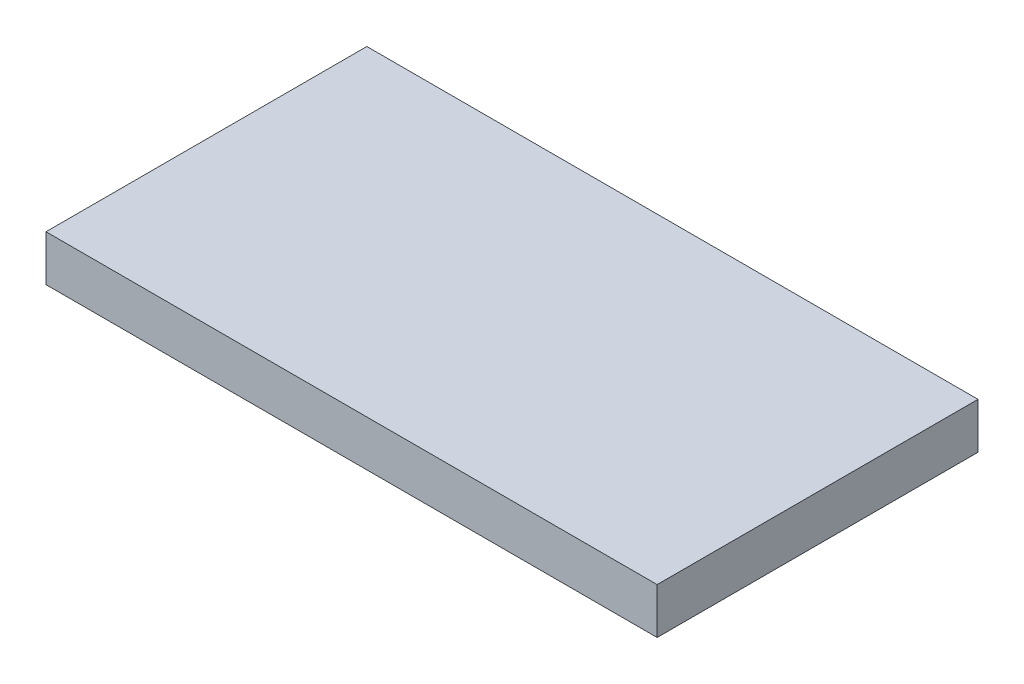
SolidWorks part; units mm, degrees
ref_plane "Front Plane" through (0, 0, 0) normal (0, 0, 1) x (1, 0, 0)
ref_plane "Top Plane" through (0, 0, 0) normal (0, 1, 0) x (1, 0, 0)
ref_plane "Right Plane" through (0, 0, 0) normal (1, 0, 0) x (0, 0, -1)
sketch "Sketch2" plane through (0, 0, 0) normal (0, 0, 1) x (1, 0, 0)
  line L0 (-137.2936, -77.8557) -> (662.7064, -77.8557)
  line L1 (662.7064, -77.8557) -> (662.7064, -17.8557)
  line L2 (662.7064, -17.8557) -> (412.7064, -17.8557)
  line L3 (412.7064, -17.8557) -> (362.7064, -17.8557)
  line L4 (362.7064, -17.8557) -> (312.7064, -17.8557)
  line L5 (312.7064, -17.8557) -> (62.7064, -17.8557)
  line L6 (62.7064, -17.8557) -> (12.7064, -17.8557)
  line L8 (-137.2936, -17.8557) -> (-137.2936, -77.8557)
  line L9 (12.7064, -17.8557) -> (-37.2936, -17.8557)
  line L10 (-37.2936, -17.8557) -> (-137.2936, -17.8557)
  line L11 (-137.2936, -47.8557) -> (662.7064, -47.8557) construction
  point P12 (-165.2459, 0)
  point P13 (186.2295, 0)
  point P14 (-63.6066, 52.623)
  point P15 (-101.6393, 28.3607)
  point P16 (-45.9016, 28.0328)
  point P17 (-77.0492, 52.623)
  point P18 (-57.0492, 28.3607)
  point P19 (28.1967, 28.3607)
  point P20 (100.9836, 52.623)
  point P21 (140.6557, 30)
  point P22 (67.8689, 30)
  point P23 (0, 0)
  point P24 (0, 0)
  point P25 (0, 0)
  point P26 (0, 0)
  point P27 (0, 0)
  dimension "D1" = 30
  dimension "D2" = 30
  dimension "D3" = 800
  dimension "D4" = 300
  dimension "D5" = 150
  dimension "D6" = 250
  dimension "D7" = 350
  dimension "D8" = 200
  dimension "D9" = 100
extrude "Boss-Extrude1" add sketch "Sketch2" along normal blind 420
